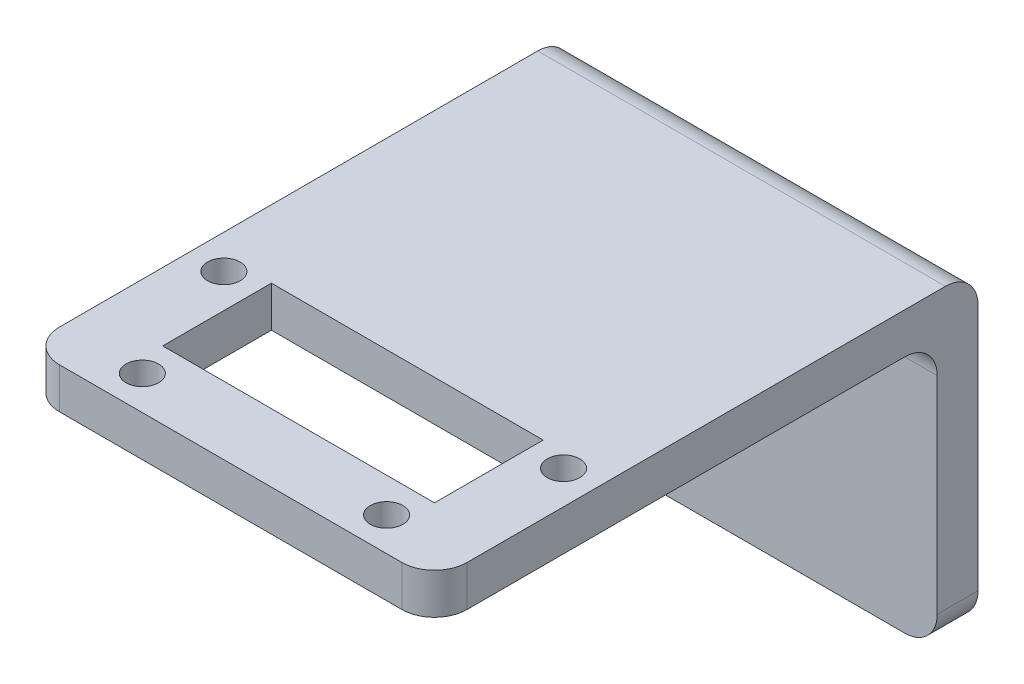
SolidWorks part; units mm, degrees
ref_plane "Plano frontal" through (0, 0, 0) normal (0, 0, 1) x (1, 0, 0)
ref_plane "Plano superior" through (0, 0, 0) normal (0, 1, 0) x (1, 0, 0)
ref_plane "Plano direito" through (0, 0, 0) normal (1, 0, 0) x (0, 0, -1)
sketch "Esboço1" plane through (0, 0, 0) normal (0, 1, 0) x (1, 0, 0)
  line L0 (0, 0) -> (0, 20) construction
  line L1 (-15, 20) -> (15, 20)
  line L2 (0, 0) -> (15, 0) construction
  line L3 (15, -20) -> (15, 20)
  line L4 (-15, 20) -> (-15, -20)
  line L5 (-15, -20) -> (15, -20)
  point P5 (0, 20)
  point P10 (15, 0)
  dimension "D1" = 30
  dimension "D2" = 40
extrude "Ressalto-extrusão1" add sketch "Esboço1" along normal blind 3
sketch "Esboço2" plane through (0, 3, 0) normal (0, 1, 0) x (1, 0, 0)
  line L4 (0, -20) -> (0, 20) construction
  line L5 (-15, -20) -> (15, -20) construction
  line L6 (15, 20) -> (-15, 20) construction
  line L7 (-10, -7) -> (10, -7)
  line L9 (-8.8957, -8) -> (9.1043, -8) construction
  line L10 (10, -7) -> (10, -15)
  line L11 (10, -15) -> (-10, -15)
  line L12 (-10, -15) -> (-10, -7)
  point P3 (0, -7)
  dimension "D1" = 0
  dimension "D2" = 20
  dimension "D3" = 1
  dimension "D4" = 8
extrude "Corte-extrusão1" cut sketch "Esboço2" against normal through all
sketch "Esboço3" plane through (0, 0, 0) normal (0, -1, 0) x (1, 0, 0)
  line L0 (-15, -20) -> (-15, 20) construction
  line L1 (-15, 20) -> (15, 20) construction
  line L2 (0, 20) -> (0.0283, 5) construction
  line L4 (-15.9979, 5) -> (16.0545, 5) construction
  line L5 (54.6527, 5) -> (-54.4441, 5) construction
  circle A0 centre (-9, 17.5) radius 1.2
  circle A2 centre (-12.5, 8) radius 1.2
  circle A6 centre (12.5451, 8.0472) radius 1.2
  circle A7 centre (9.0094, 17.5339) radius 1.2
  dimension "D1" = 2.4
  dimension "D7" = 2.4
  dimension "D2" = 6
  dimension "D3" = 2.5
  dimension "D9" = 2.5
  dimension "D11" = 3
extrude "Corte-extrusão2" cut sketch "Esboço3" against normal through all
sketch "Esboço4" plane through (0, 0, 0) normal (0, -1, 0) x (1, 0, 0)
  line L0 (-15, -17) -> (15, -17)
  line L4 (-15, 20) -> (-15, -20)
  line L5 (-15, -20) -> (15, -20)
  line L6 (15, -20) -> (15, 20)
  line L7 (15, 20) -> (-15, 20)
  line L8 (-15, 20) -> (-15, -20)
  line L9 (-15, -20) -> (15, -20)
  line L10 (15, -20) -> (15, 20)
  line L11 (15, 20) -> (-15, 20)
  dimension "D2" = 3
  dimension "D1" = 0
extrude "Ressalto-extrusão2" add sketch "Esboço4" along normal blind 20
fillet "Filete5" radius 2.4 1 edges at (0, 0, -17)
fillet "Filete6" radius 2.4 1 edges at (0, 3, -20)
fillet "Filete7" radius 2.4 2 edges at (15, 1.5, 20) (-15, 1.5, 20)
fillet "Filete8" radius 2.4 2 edges at (-15, -20, -18.5) (15, -20, -18.5)
